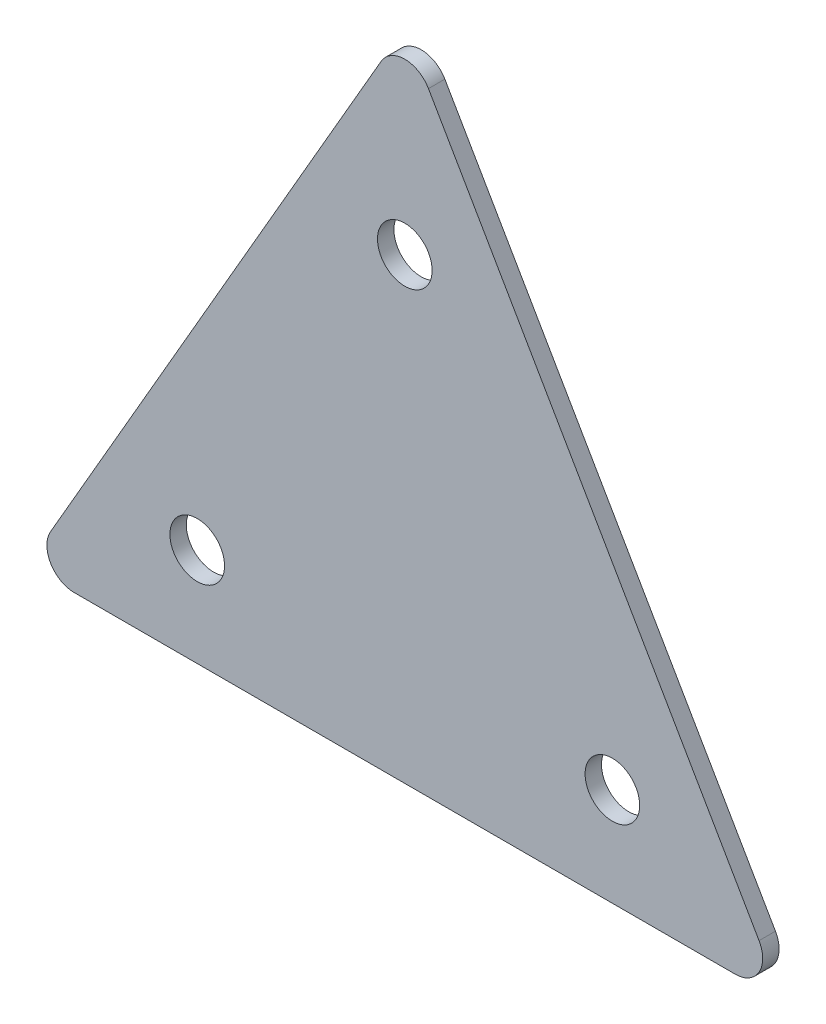
SolidWorks part; units mm, degrees
ref_plane "Front Plane" through (0, 0, 0) normal (0, 0, 1) x (1, 0, 0)
ref_plane "Top Plane" through (0, 0, 0) normal (0, 1, 0) x (1, 0, 0)
ref_plane "Right Plane" through (0, 0, 0) normal (1, 0, 0) x (0, 0, -1)
sketch "Sketch1" plane through (0, 0, 0) normal (0, 0, 1) x (1, 0, 0)
  line L0 (-32.7569, -9) -> (36.42, -9)
  line L1 (36.42, -9) -> (1.8315, 50.909)
  line L2 (1.8315, 50.909) -> (-32.7569, -9)
  circle A0 centre (-17.1685, 0) radius 2.5
  circle A1 centre (20.8315, 0) radius 2.5
  circle A2 centre (1.8315, 32.909) radius 2.5
  dimension "D5" = 5
  dimension "D1" = 38
  dimension "D2" = 38
  dimension "D3" = 38
  dimension "D4" = 9
  dimension "D6" = 9
  dimension "D7" = 9
  dimension "D8" = 9
extrude "Boss-Extrude1" add sketch "Sketch1" along normal blind 1.5
fillet "Fillet1" radius 2.5 3 edges at (36.42, -9, 0.75) (-32.7569, -9, 0.75) (1.8315, 50.909, 0.75)
sketch "Sketch2" plane through (0, 0, 0) normal (0, 0, -1) x (-1, 0, 0)
  line L0 (-55.1719, 32.909) -> (20.3281, 32.909) construction
  line L1 (-55.1719, 48.1) -> (20.3281, 48.1)
  line L2 (-55.1719, 48.1) -> (-55.1719, 17.718)
  line L3 (-55.1719, 17.718) -> (20.3281, 17.718)
  line L4 (20.3281, 48.1) -> (20.3281, 17.718)
  line L5 (-55.1719, 48.1) -> (20.3281, 17.718) construction
  line L6 (-55.1719, 17.718) -> (20.3281, 48.1) construction
  line L7 (-46.8315, 48.1) -> (-46.8315, 17.718)
  line L8 (12.1685, 48.1) -> (12.1685, 17.718)
  line L9 (16.1685, 48.1) -> (16.1685, 17.718) construction
  line L10 (-50.8315, 48.1) -> (-50.8315, 17.718) construction
  line L11 (12.1685, 34.409) -> (20.3281, 34.409)
  line L12 (20.3281, 34.409) -> (20.3281, 31.409)
  line L13 (20.3281, 31.409) -> (12.1685, 31.409)
  line L14 (-46.8315, 34.409) -> (-55.1719, 34.409)
  line L15 (-46.8315, 31.409) -> (-55.1719, 31.409)
  line L16 (-46.8315, 48.1) -> (12.1685, 17.718) construction
  line L17 (12.1685, 17.718) -> (12.1685, 48.1) construction
  line L18 (12.1685, 48.1) -> (-46.8315, 17.718) construction
  circle A0 centre (-1.8315, 32.909) radius 4.125
  point P0 (-17.4219, 32.909)
  point P26 (-17.3315, 32.909)
  point P27 (0, 0)
  point P28 (0, 0)
  dimension "D2" = 8.25
  dimension "D1" = 75.5
  dimension "D3" = 14
  dimension "D4" = 45
  dimension "D5" = 67
  dimension "D6" = 3
  dimension "D7" = 1.5
  dimension "D8" = 3
  dimension "D9" = 4
  dimension "D10" = 4
  dimension "D11" = 59
equation "\"D2@Sketch1\"=\"D1@Sketch1\""
equation "\"D3@Sketch1\"=\"D1@Sketch1\""
equation "\"D6@Sketch1\"=\"D4@Sketch1\""
equation "\"D7@Sketch1\"=\"D4@Sketch1\""
equation "\"D8@Sketch1\"=\"D4@Sketch1\""
equation "\"D7@Sketch2\"=\"D6@Sketch2\"/2"
equation "\"D8@Sketch2\"=3"
